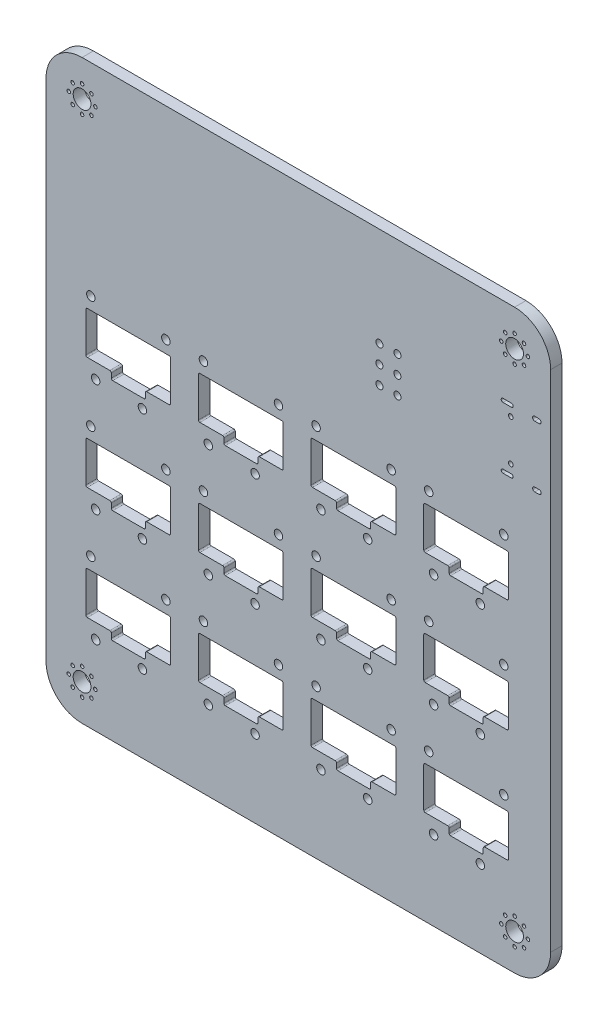
SolidWorks part; units mm, degrees
ref_plane "Plan de face" through (0, 0, 0) normal (0, 0, 1) x (1, 0, 0)
ref_plane "Plan de dessus" through (0, 0, 0) normal (0, 1, 0) x (1, 0, 0)
ref_plane "Plan de droite" through (0, 0, 0) normal (1, 0, 0) x (0, 0, -1)
ref_plane "Plan1" through (0, 0, 1.6) normal (0, 0, 1) x (1, 0, 0)
sketch "Esquisse1" plane through (0, 0, 1.6) normal (0, 0, 1) x (1, 0, 0)
  line L0 (236.485, -57.325) -> (235.885, -57.325)
  line L1 (235.885, -56.725) -> (236.485, -56.725)
  line L2 (235.885, -48.085) -> (236.485, -48.085)
  line L3 (236.485, -48.685) -> (235.885, -48.685)
  line L4 (231.405, -56.775) -> (232.605, -56.775)
  line L5 (232.605, -57.275) -> (231.405, -57.275)
  line L6 (232.605, -48.635) -> (231.405, -48.635)
  line L7 (231.405, -48.135) -> (232.605, -48.135)
  line L8 (223.828, -89.154) -> (223.828, -88.5119)
  line L9 (223.628, -88.3119) -> (220.4421, -88.3119)
  line L10 (220.2421, -88.1119) -> (220.2421, -82.5282)
  line L11 (220.4421, -82.3282) -> (231.9815, -82.3282)
  line L12 (232.1815, -82.5282) -> (232.1815, -88.1119)
  line L13 (231.9815, -88.3119) -> (228.8283, -88.3119)
  line L14 (228.6283, -88.5119) -> (228.6283, -89.154)
  line L15 (228.4283, -89.354) -> (224.028, -89.354)
  line L16 (180.8033, -89.354) -> (176.403, -89.354)
  line L17 (176.203, -89.154) -> (176.203, -88.5119)
  line L18 (176.003, -88.3119) -> (172.8171, -88.3119)
  line L19 (172.6171, -88.1119) -> (172.6171, -82.5282)
  line L20 (172.8171, -82.3282) -> (184.3565, -82.3282)
  line L21 (184.5565, -82.5282) -> (184.5565, -88.1119)
  line L22 (184.3565, -88.3119) -> (181.2033, -88.3119)
  line L23 (181.0033, -88.5119) -> (181.0033, -89.154)
  line L24 (200.2315, -88.3119) -> (197.0783, -88.3119)
  line L25 (196.8783, -88.5119) -> (196.8783, -89.154)
  line L26 (196.6783, -89.354) -> (192.278, -89.354)
  line L27 (192.078, -89.154) -> (192.078, -88.5119)
  line L28 (191.878, -88.3119) -> (188.6921, -88.3119)
  line L29 (188.4921, -88.1119) -> (188.4921, -82.5282)
  line L30 (188.6921, -82.3282) -> (200.2315, -82.3282)
  line L31 (200.4315, -82.5282) -> (200.4315, -88.1119)
  line L32 (216.3065, -82.5282) -> (216.3065, -88.1119)
  line L33 (216.1065, -88.3119) -> (212.9533, -88.3119)
  line L34 (212.7533, -88.5119) -> (212.7533, -89.154)
  line L35 (212.5533, -89.354) -> (208.153, -89.354)
  line L36 (207.953, -89.154) -> (207.953, -88.5119)
  line L37 (207.753, -88.3119) -> (204.5671, -88.3119)
  line L38 (204.3671, -88.1119) -> (204.3671, -82.5282)
  line L39 (204.5671, -82.3282) -> (216.1065, -82.3282)
  line L40 (216.3065, -98.4032) -> (216.3065, -103.9869)
  line L41 (216.1065, -104.1869) -> (212.9533, -104.1869)
  line L42 (212.7533, -104.3869) -> (212.7533, -105.029)
  line L43 (212.5533, -105.229) -> (208.153, -105.229)
  line L44 (207.953, -105.029) -> (207.953, -104.3869)
  line L45 (207.753, -104.1869) -> (204.5671, -104.1869)
  line L46 (204.3671, -103.9869) -> (204.3671, -98.4032)
  line L47 (204.5671, -98.2032) -> (216.1065, -98.2032)
  line L48 (220.4421, -98.2032) -> (231.9815, -98.2032)
  line L49 (232.1815, -98.4032) -> (232.1815, -103.9869)
  line L50 (231.9815, -104.1869) -> (228.8283, -104.1869)
  line L51 (228.6283, -104.3869) -> (228.6283, -105.029)
  line L52 (228.4283, -105.229) -> (224.028, -105.229)
  line L53 (223.828, -105.029) -> (223.828, -104.3869)
  line L54 (223.628, -104.1869) -> (220.4421, -104.1869)
  line L55 (220.2421, -103.9869) -> (220.2421, -98.4032)
  line L56 (184.3565, -104.1869) -> (181.2033, -104.1869)
  line L57 (181.0033, -104.3869) -> (181.0033, -105.029)
  line L58 (180.8033, -105.229) -> (176.403, -105.229)
  line L59 (176.203, -105.029) -> (176.203, -104.3869)
  line L60 (176.003, -104.1869) -> (172.8171, -104.1869)
  line L61 (172.6171, -103.9869) -> (172.6171, -98.4032)
  line L62 (172.8171, -98.2032) -> (184.3565, -98.2032)
  line L63 (184.5565, -98.4032) -> (184.5565, -103.9869)
  line L64 (192.078, -105.029) -> (192.078, -104.3869)
  line L65 (191.878, -104.1869) -> (188.6921, -104.1869)
  line L66 (188.4921, -103.9869) -> (188.4921, -98.4032)
  line L67 (188.6921, -98.2032) -> (200.2315, -98.2032)
  line L68 (200.4315, -98.4032) -> (200.4315, -103.9869)
  line L69 (200.2315, -104.1869) -> (197.0783, -104.1869)
  line L70 (196.8783, -104.3869) -> (196.8783, -105.029)
  line L71 (196.6783, -105.229) -> (192.278, -105.229)
  line L72 (220.2421, -72.2369) -> (220.2421, -66.6532)
  line L73 (220.4421, -66.4532) -> (231.9815, -66.4532)
  line L74 (232.1815, -66.6532) -> (232.1815, -72.2369)
  line L75 (231.9815, -72.4369) -> (228.8283, -72.4369)
  line L76 (228.6283, -72.6369) -> (228.6283, -73.279)
  line L77 (228.4283, -73.479) -> (224.028, -73.479)
  line L78 (223.828, -73.279) -> (223.828, -72.6369)
  line L79 (223.628, -72.4369) -> (220.4421, -72.4369)
  line L80 (207.953, -73.279) -> (207.953, -72.6369)
  line L81 (207.753, -72.4369) -> (204.5671, -72.4369)
  line L82 (204.3671, -72.2369) -> (204.3671, -66.6532)
  line L83 (204.5671, -66.4532) -> (216.1065, -66.4532)
  line L84 (216.3065, -66.6532) -> (216.3065, -72.2369)
  line L85 (216.1065, -72.4369) -> (212.9533, -72.4369)
  line L86 (212.7533, -72.6369) -> (212.7533, -73.279)
  line L87 (212.5533, -73.479) -> (208.153, -73.479)
  line L88 (200.4315, -66.6532) -> (200.4315, -72.2369)
  line L89 (200.2315, -72.4369) -> (197.0783, -72.4369)
  line L90 (196.8783, -72.6369) -> (196.8783, -73.279)
  line L91 (196.6783, -73.479) -> (192.278, -73.479)
  line L92 (192.078, -73.279) -> (192.078, -72.6369)
  line L93 (191.878, -72.4369) -> (188.6921, -72.4369)
  line L94 (188.4921, -72.2369) -> (188.4921, -66.6532)
  line L95 (188.6921, -66.4532) -> (200.2315, -66.4532)
  line L96 (184.3565, -72.4369) -> (181.2033, -72.4369)
  line L97 (181.0033, -72.6369) -> (181.0033, -73.279)
  line L98 (180.8033, -73.479) -> (176.403, -73.479)
  line L99 (176.203, -73.279) -> (176.203, -72.6369)
  line L100 (176.003, -72.4369) -> (172.8171, -72.4369)
  line L101 (172.6171, -72.2369) -> (172.6171, -66.6532)
  line L102 (172.8171, -66.4532) -> (184.3565, -66.4532)
  line L103 (184.5565, -66.6532) -> (184.5565, -72.2369)
  line L104 (167.005, -41.275) -> (167.005, -112.395)
  line L105 (172.085, -117.475) -> (233.045, -117.475)
  line L106 (238.125, -112.395) -> (238.125, -41.275)
  line L107 (233.045, -36.195) -> (172.085, -36.195)
  circle A0 centre (233.045, -114.27) radius 0.25
  circle A1 centre (172.085, -114.27) radius 0.25
  circle A2 centre (233.045, -39.4) radius 0.25
  circle A3 centre (172.085, -39.4) radius 0.25
  circle A4 centre (170.7592, -39.9492) radius 0.25
  circle A5 centre (172.085, -41.275) radius 1.25
  circle A6 centre (173.4108, -39.9492) radius 0.25
  circle A7 centre (231.17, -41.275) radius 0.25
  circle A8 centre (231.7192, -39.9492) radius 0.25
  circle A9 centre (234.3708, -42.6008) radius 0.25
  circle A10 centre (233.045, -41.275) radius 1.25
  circle A11 centre (234.3708, -39.9492) radius 0.25
  arc A12 (235.885, -57.325) -> (235.885, -56.725) centre (235.885, -57.025) cw
  arc A13 (236.485, -56.725) -> (236.485, -57.325) centre (236.485, -57.025) cw
  arc A14 (236.485, -48.085) -> (236.485, -48.685) centre (236.485, -48.385) cw
  arc A15 (235.885, -48.685) -> (235.885, -48.085) centre (235.885, -48.385) cw
  circle A16 centre (231.521, -64.7192) radius 0.6
  arc A17 (231.405, -57.275) -> (231.405, -56.775) centre (231.405, -57.025) cw
  arc A18 (232.605, -56.775) -> (232.605, -57.275) centre (232.605, -57.025) cw
  circle A19 centre (232.505, -49.815) radius 0.325
  circle A20 centre (233.045, -43.15) radius 0.25
  circle A21 centre (234.92, -41.275) radius 0.25
  circle A22 centre (231.521, -80.5942) radius 0.6
  circle A23 centre (233.045, -110.52) radius 0.25
  circle A24 centre (234.3708, -111.0692) radius 0.25
  circle A25 centre (231.7192, -111.0692) radius 0.25
  circle A26 centre (231.7192, -113.7208) radius 0.25
  circle A27 centre (233.045, -112.395) radius 1.25
  circle A28 centre (234.3708, -113.7208) radius 0.25
  circle A29 centre (234.92, -112.395) radius 0.25
  circle A30 centre (172.085, -110.52) radius 0.25
  circle A31 centre (170.7592, -111.0692) radius 0.25
  circle A32 centre (172.085, -112.395) radius 1.25
  circle A33 centre (173.4108, -111.0692) radius 0.25
  circle A34 centre (170.21, -112.395) radius 0.25
  circle A35 centre (231.17, -112.395) radius 0.25
  circle A36 centre (173.4108, -113.7208) radius 0.25
  circle A37 centre (173.96, -112.395) radius 0.25
  circle A38 centre (170.7592, -113.7208) radius 0.25
  arc A39 (232.605, -48.135) -> (232.605, -48.635) centre (232.605, -48.385) cw
  arc A40 (231.405, -48.635) -> (231.405, -48.135) centre (231.405, -48.385) cw
  circle A41 centre (189.8777, -74.5363) radius 0.6
  circle A42 centre (196.469, -74.8157) radius 0.6
  circle A43 centre (212.344, -74.8157) radius 0.6
  circle A44 centre (205.7527, -74.5363) radius 0.6
  circle A45 centre (205.0669, -80.5815) radius 0.6
  circle A46 centre (199.771, -80.5942) radius 0.6
  circle A47 centre (215.646, -80.5942) radius 0.6
  circle A48 centre (221.6277, -74.5363) radius 0.6
  circle A49 centre (228.219, -74.8157) radius 0.6
  arc A50 (223.828, -88.5119) -> (223.628, -88.3119) centre (223.628, -88.5119) ccw
  arc A51 (220.4421, -88.3119) -> (220.2421, -88.1119) centre (220.4421, -88.1119) cw
  arc A52 (220.2421, -82.5282) -> (220.4421, -82.3282) centre (220.4421, -82.5282) cw
  arc A53 (231.9815, -82.3282) -> (232.1815, -82.5282) centre (231.9815, -82.5282) cw
  arc A54 (232.1815, -88.1119) -> (231.9815, -88.3119) centre (231.9815, -88.1119) cw
  arc A55 (228.8283, -88.3119) -> (228.6283, -88.5119) centre (228.8283, -88.5119) ccw
  arc A56 (228.6283, -89.154) -> (228.4283, -89.354) centre (228.4283, -89.154) cw
  arc A57 (224.028, -89.354) -> (223.828, -89.154) centre (224.028, -89.154) cw
  arc A58 (176.403, -89.354) -> (176.203, -89.154) centre (176.403, -89.154) cw
  arc A59 (176.203, -88.5119) -> (176.003, -88.3119) centre (176.003, -88.5119) ccw
  arc A60 (172.8171, -88.3119) -> (172.6171, -88.1119) centre (172.8171, -88.1119) cw
  arc A61 (172.6171, -82.5282) -> (172.8171, -82.3282) centre (172.8171, -82.5282) cw
  arc A62 (184.3565, -82.3282) -> (184.5565, -82.5282) centre (184.3565, -82.5282) cw
  arc A63 (184.5565, -88.1119) -> (184.3565, -88.3119) centre (184.3565, -88.1119) cw
  arc A64 (181.2033, -88.3119) -> (181.0033, -88.5119) centre (181.2033, -88.5119) ccw
  arc A65 (181.0033, -89.154) -> (180.8033, -89.354) centre (180.8033, -89.154) cw
  arc A66 (197.0783, -88.3119) -> (196.8783, -88.5119) centre (197.0783, -88.5119) ccw
  arc A67 (196.8783, -89.154) -> (196.6783, -89.354) centre (196.6783, -89.154) cw
  arc A68 (192.278, -89.354) -> (192.078, -89.154) centre (192.278, -89.154) cw
  arc A69 (192.078, -88.5119) -> (191.878, -88.3119) centre (191.878, -88.5119) ccw
  arc A70 (188.6921, -88.3119) -> (188.4921, -88.1119) centre (188.6921, -88.1119) cw
  arc A71 (188.4921, -82.5282) -> (188.6921, -82.3282) centre (188.6921, -82.5282) cw
  arc A72 (200.2315, -82.3282) -> (200.4315, -82.5282) centre (200.2315, -82.5282) cw
  arc A73 (200.4315, -88.1119) -> (200.2315, -88.3119) centre (200.2315, -88.1119) cw
  arc A74 (216.1065, -82.3282) -> (216.3065, -82.5282) centre (216.1065, -82.5282) cw
  arc A75 (216.3065, -88.1119) -> (216.1065, -88.3119) centre (216.1065, -88.1119) cw
  arc A76 (212.9533, -88.3119) -> (212.7533, -88.5119) centre (212.9533, -88.5119) ccw
  arc A77 (212.7533, -89.154) -> (212.5533, -89.354) centre (212.5533, -89.154) cw
  arc A78 (208.153, -89.354) -> (207.953, -89.154) centre (208.153, -89.154) cw
  arc A79 (207.953, -88.5119) -> (207.753, -88.3119) centre (207.753, -88.5119) ccw
  arc A80 (204.5671, -88.3119) -> (204.3671, -88.1119) centre (204.5671, -88.1119) cw
  arc A81 (204.3671, -82.5282) -> (204.5671, -82.3282) centre (204.5671, -82.5282) cw
  circle A82 centre (228.219, -90.6907) radius 0.6
  circle A83 centre (205.7527, -90.4113) radius 0.6
  circle A84 centre (212.344, -90.6907) radius 0.6
  circle A85 centre (221.6277, -90.4113) radius 0.6
  circle A86 centre (196.469, -90.6907) radius 0.6
  circle A87 centre (180.594, -90.6907) radius 0.6
  circle A88 centre (174.0027, -90.4113) radius 0.6
  circle A89 centre (189.8777, -90.4113) radius 0.6
  circle A90 centre (215.646, -96.4692) radius 0.6
  circle A91 centre (205.0669, -96.4565) radius 0.6
  arc A92 (216.3065, -103.9869) -> (216.1065, -104.1869) centre (216.1065, -103.9869) cw
  arc A93 (212.9533, -104.1869) -> (212.7533, -104.3869) centre (212.9533, -104.3869) ccw
  arc A94 (212.7533, -105.029) -> (212.5533, -105.229) centre (212.5533, -105.029) cw
  arc A95 (208.153, -105.229) -> (207.953, -105.029) centre (208.153, -105.029) cw
  arc A96 (207.953, -104.3869) -> (207.753, -104.1869) centre (207.753, -104.3869) ccw
  arc A97 (204.5671, -104.1869) -> (204.3671, -103.9869) centre (204.5671, -103.9869) cw
  arc A98 (204.3671, -98.4032) -> (204.5671, -98.2032) centre (204.5671, -98.4032) cw
  arc A99 (216.1065, -98.2032) -> (216.3065, -98.4032) centre (216.1065, -98.4032) cw
  circle A100 centre (220.9419, -96.4565) radius 0.6
  circle A101 centre (231.521, -96.4692) radius 0.6
  arc A102 (231.9815, -98.2032) -> (232.1815, -98.4032) centre (231.9815, -98.4032) cw
  arc A103 (232.1815, -103.9869) -> (231.9815, -104.1869) centre (231.9815, -103.9869) cw
  arc A104 (228.8283, -104.1869) -> (228.6283, -104.3869) centre (228.8283, -104.3869) ccw
  arc A105 (228.6283, -105.029) -> (228.4283, -105.229) centre (228.4283, -105.029) cw
  arc A106 (224.028, -105.229) -> (223.828, -105.029) centre (224.028, -105.029) cw
  arc A107 (223.828, -104.3869) -> (223.628, -104.1869) centre (223.628, -104.3869) ccw
  arc A108 (220.4421, -104.1869) -> (220.2421, -103.9869) centre (220.4421, -103.9869) cw
  arc A109 (220.2421, -98.4032) -> (220.4421, -98.2032) centre (220.4421, -98.4032) cw
  circle A110 centre (199.771, -96.4692) radius 0.6
  circle A111 centre (173.3169, -96.4565) radius 0.6
  arc A112 (181.2033, -104.1869) -> (181.0033, -104.3869) centre (181.2033, -104.3869) ccw
  arc A113 (181.0033, -105.029) -> (180.8033, -105.229) centre (180.8033, -105.029) cw
  arc A114 (176.403, -105.229) -> (176.203, -105.029) centre (176.403, -105.029) cw
  arc A115 (176.203, -104.3869) -> (176.003, -104.1869) centre (176.003, -104.3869) ccw
  arc A116 (172.8171, -104.1869) -> (172.6171, -103.9869) centre (172.8171, -103.9869) cw
  arc A117 (172.6171, -98.4032) -> (172.8171, -98.2032) centre (172.8171, -98.4032) cw
  arc A118 (184.3565, -98.2032) -> (184.5565, -98.4032) centre (184.3565, -98.4032) cw
  arc A119 (184.5565, -103.9869) -> (184.3565, -104.1869) centre (184.3565, -103.9869) cw
  arc A120 (192.078, -104.3869) -> (191.878, -104.1869) centre (191.878, -104.3869) ccw
  arc A121 (188.6921, -104.1869) -> (188.4921, -103.9869) centre (188.6921, -103.9869) cw
  arc A122 (188.4921, -98.4032) -> (188.6921, -98.2032) centre (188.6921, -98.4032) cw
  arc A123 (200.2315, -98.2032) -> (200.4315, -98.4032) centre (200.2315, -98.4032) cw
  arc A124 (200.4315, -103.9869) -> (200.2315, -104.1869) centre (200.2315, -103.9869) cw
  arc A125 (197.0783, -104.1869) -> (196.8783, -104.3869) centre (197.0783, -104.3869) ccw
  arc A126 (196.8783, -105.029) -> (196.6783, -105.229) centre (196.6783, -105.029) cw
  arc A127 (192.278, -105.229) -> (192.078, -105.029) centre (192.278, -105.029) cw
  circle A128 centre (189.1919, -96.4565) radius 0.6
  circle A129 centre (183.896, -96.4692) radius 0.6
  circle A130 centre (189.8777, -106.2863) radius 0.6
  circle A131 centre (196.469, -106.5657) radius 0.6
  circle A132 centre (180.594, -106.5657) radius 0.6
  circle A133 centre (174.0027, -106.2863) radius 0.6
  circle A134 centre (212.344, -106.5657) radius 0.6
  circle A135 centre (205.7527, -106.2863) radius 0.6
  circle A136 centre (221.6277, -106.2863) radius 0.6
  circle A137 centre (228.219, -106.5657) radius 0.6
  circle A138 centre (232.505, -55.595) radius 0.325
  circle A139 centre (231.7192, -42.6008) radius 0.25
  arc A140 (220.2421, -66.6532) -> (220.4421, -66.4532) centre (220.4421, -66.6532) cw
  arc A141 (231.9815, -66.4532) -> (232.1815, -66.6532) centre (231.9815, -66.6532) cw
  arc A142 (232.1815, -72.2369) -> (231.9815, -72.4369) centre (231.9815, -72.2369) cw
  arc A143 (228.8283, -72.4369) -> (228.6283, -72.6369) centre (228.8283, -72.6369) ccw
  arc A144 (228.6283, -73.279) -> (228.4283, -73.479) centre (228.4283, -73.279) cw
  arc A145 (224.028, -73.479) -> (223.828, -73.279) centre (224.028, -73.279) cw
  arc A146 (223.828, -72.6369) -> (223.628, -72.4369) centre (223.628, -72.6369) ccw
  arc A147 (220.4421, -72.4369) -> (220.2421, -72.2369) centre (220.4421, -72.2369) cw
  circle A148 centre (220.9419, -64.7065) radius 0.6
  circle A149 centre (220.9419, -80.5815) radius 0.6
  circle A150 centre (173.4108, -42.6008) radius 0.25
  circle A151 centre (173.96, -41.275) radius 0.25
  circle A152 centre (172.085, -43.15) radius 0.25
  circle A153 centre (170.7592, -42.6008) radius 0.25
  circle A154 centre (170.21, -41.275) radius 0.25
  circle A155 centre (213.995, -52.705) radius 0.5
  circle A156 centre (216.535, -52.705) radius 0.5
  circle A157 centre (213.995, -50.165) radius 0.5
  circle A158 centre (216.535, -50.165) radius 0.5
  arc A159 (207.953, -72.6369) -> (207.753, -72.4369) centre (207.753, -72.6369) ccw
  arc A160 (204.5671, -72.4369) -> (204.3671, -72.2369) centre (204.5671, -72.2369) cw
  arc A161 (204.3671, -66.6532) -> (204.5671, -66.4532) centre (204.5671, -66.6532) cw
  arc A162 (216.1065, -66.4532) -> (216.3065, -66.6532) centre (216.1065, -66.6532) cw
  arc A163 (216.3065, -72.2369) -> (216.1065, -72.4369) centre (216.1065, -72.2369) cw
  arc A164 (212.9533, -72.4369) -> (212.7533, -72.6369) centre (212.9533, -72.6369) ccw
  arc A165 (212.7533, -73.279) -> (212.5533, -73.479) centre (212.5533, -73.279) cw
  arc A166 (208.153, -73.479) -> (207.953, -73.279) centre (208.153, -73.279) cw
  circle A167 centre (205.0669, -64.7065) radius 0.6
  circle A168 centre (215.646, -64.7192) radius 0.6
  circle A169 centre (213.995, -55.245) radius 0.5
  circle A170 centre (216.535, -55.245) radius 0.5
  arc A171 (200.4315, -72.2369) -> (200.2315, -72.4369) centre (200.2315, -72.2369) cw
  arc A172 (197.0783, -72.4369) -> (196.8783, -72.6369) centre (197.0783, -72.6369) ccw
  arc A173 (196.8783, -73.279) -> (196.6783, -73.479) centre (196.6783, -73.279) cw
  arc A174 (192.278, -73.479) -> (192.078, -73.279) centre (192.278, -73.279) cw
  arc A175 (192.078, -72.6369) -> (191.878, -72.4369) centre (191.878, -72.6369) ccw
  arc A176 (188.6921, -72.4369) -> (188.4921, -72.2369) centre (188.6921, -72.2369) cw
  arc A177 (188.4921, -66.6532) -> (188.6921, -66.4532) centre (188.6921, -66.6532) cw
  arc A178 (200.2315, -66.4532) -> (200.4315, -66.6532) centre (200.2315, -66.6532) cw
  circle A179 centre (199.771, -64.7192) radius 0.6
  circle A180 centre (189.1919, -64.7065) radius 0.6
  circle A181 centre (189.1919, -80.5815) radius 0.6
  arc A182 (181.2033, -72.4369) -> (181.0033, -72.6369) centre (181.2033, -72.6369) ccw
  arc A183 (181.0033, -73.279) -> (180.8033, -73.479) centre (180.8033, -73.279) cw
  arc A184 (176.403, -73.479) -> (176.203, -73.279) centre (176.403, -73.279) cw
  arc A185 (176.203, -72.6369) -> (176.003, -72.4369) centre (176.003, -72.6369) ccw
  arc A186 (172.8171, -72.4369) -> (172.6171, -72.2369) centre (172.8171, -72.2369) cw
  arc A187 (172.6171, -66.6532) -> (172.8171, -66.4532) centre (172.8171, -66.6532) cw
  arc A188 (184.3565, -66.4532) -> (184.5565, -66.6532) centre (184.3565, -66.6532) cw
  arc A189 (184.5565, -72.2369) -> (184.3565, -72.4369) centre (184.3565, -72.2369) cw
  circle A190 centre (183.896, -64.7192) radius 0.6
  circle A191 centre (173.3169, -64.7065) radius 0.6
  circle A192 centre (174.0027, -74.5363) radius 0.6
  circle A193 centre (180.594, -74.8157) radius 0.6
  circle A194 centre (183.896, -80.5942) radius 0.6
  circle A195 centre (173.3169, -80.5815) radius 0.6
  arc A196 (167.005, -112.395) -> (172.085, -117.475) centre (172.085, -112.395) ccw
  arc A197 (233.045, -117.475) -> (238.125, -112.395) centre (233.045, -112.395) ccw
  arc A198 (238.125, -41.275) -> (233.045, -36.195) centre (233.045, -41.275) ccw
  arc A199 (172.085, -36.195) -> (167.005, -41.275) centre (172.085, -41.275) ccw
extrude "Boss.-Extru.1" add sketch "Esquisse1" against normal blind 1.6
